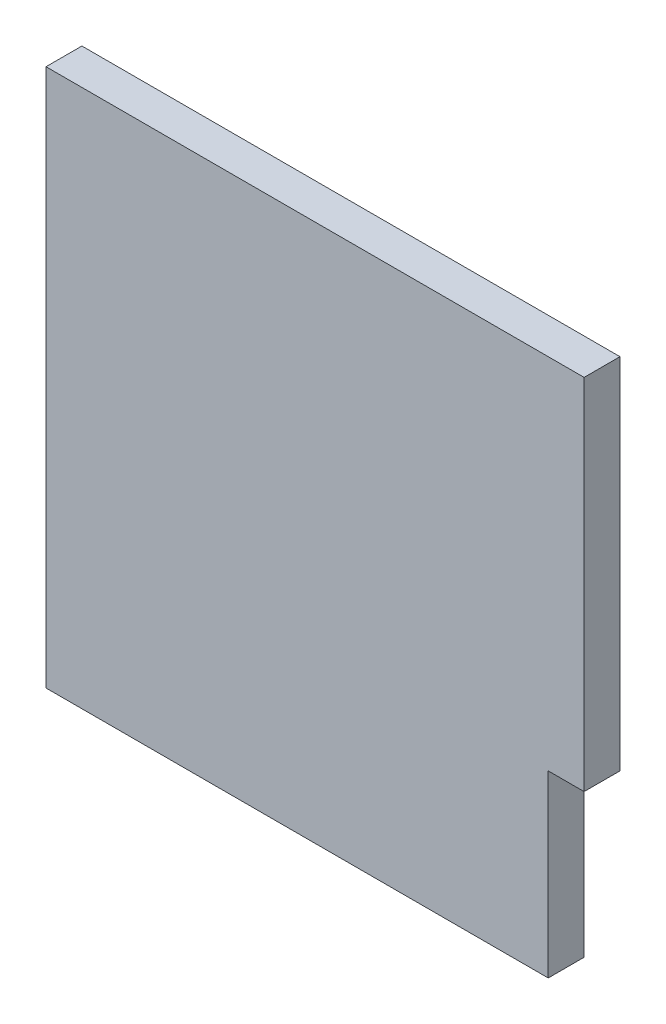
SolidWorks part; units mm, degrees
material "PBT General Purpose"
ref_plane "Front Plane" through (0, 0, 0) normal (0, 0, 1) x (1, 0, 0)
ref_plane "Top Plane" through (0, 0, 0) normal (0, 1, 0) x (1, 0, 0)
ref_plane "Right Plane" through (0, 0, 0) normal (1, 0, 0) x (0, 0, -1)
sketch "Sketch1" plane through (0, 0, 0) normal (0, 0, 1) x (1, 0, 0)
  line L0 (0, 0) -> (0, 1)
  line L1 (0, 1) -> (-1.5, 1)
  line L2 (-1.5, 1) -> (-1.5, -0.5)
  line L3 (-1.5, -0.5) -> (-0.1, -0.5)
  line L4 (-0.1, -0.5) -> (-0.1, 0)
  line L5 (-0.1, 0) -> (0, 0)
  dimension "D1" = 1
  dimension "D2" = 0.1
  dimension "D3" = 0.5
  dimension "D4" = 1.4
extrude "Boss-Extrude1" add sketch "Sketch1" along normal mid plane 0.1
